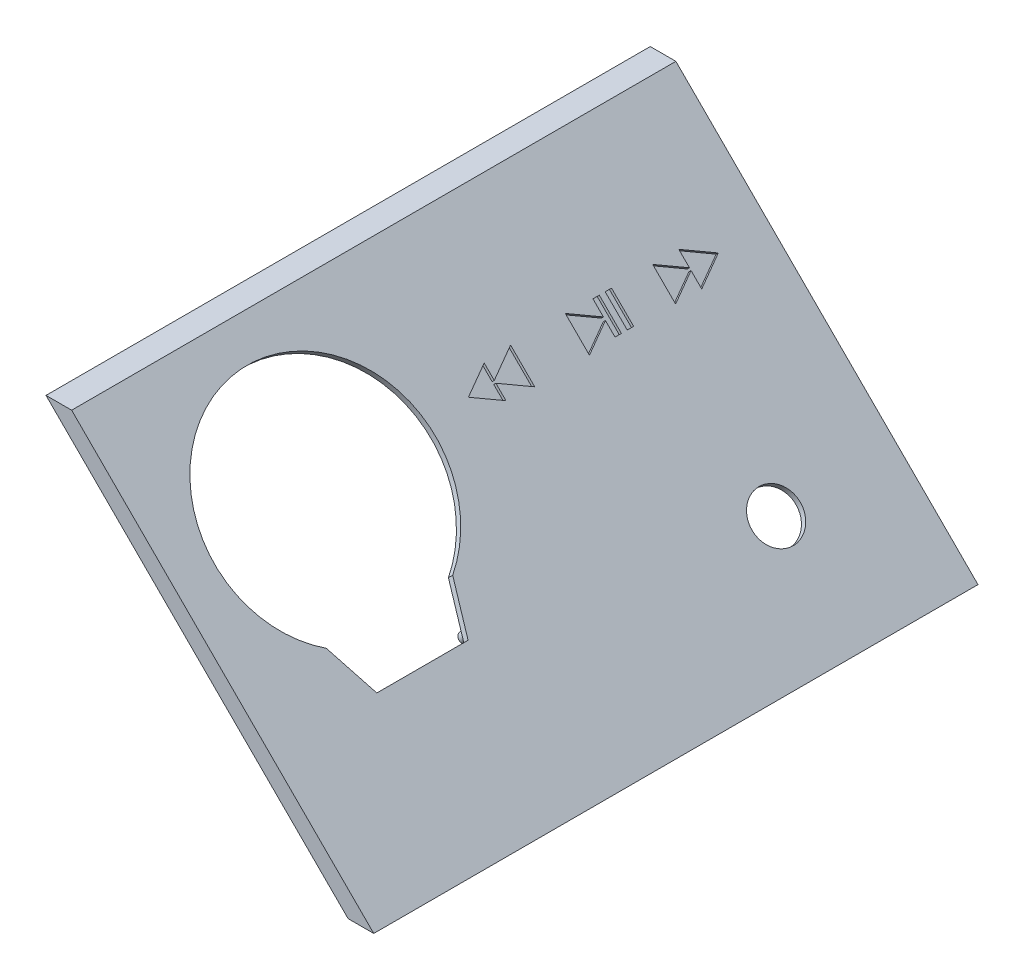
SolidWorks part; units mm, degrees
ref_plane "Front Plane" through (0, 0, 0) normal (0, 0, 1) x (1, 0, 0)
ref_plane "Top Plane" through (0, 0, 0) normal (0, 1, 0) x (1, 0, 0)
ref_plane "Right Plane" through (0, 0, 0) normal (1, 0, 0) x (0, 0, -1)
sketch "Sketch1" plane through (0, 0, 0) normal (0, 0, 1) x (1, 0, 0)
  line L0 (0, 0) -> (4.2426, 0)
  line L1 (4.2426, 0) -> (-45.7574, 50)
  line L2 (-45.7574, 50) -> (-50, 50)
  line L3 (-50, 50) -> (0, 0)
  dimension "D1" = 45
  dimension "D2" = 3
  dimension "D3" = 50
extrude "Boss-Extrude1" add sketch "Sketch1" along normal mid plane 100
sketch "Sketch2" plane through (2.1213, 2.1213, 0) normal (0.7071, 0.7071, 0) x (0, 0, -1)
  line L2 (-50, -3) -> (-50, 67.7107) construction
  line L3 (-32.3831, 21.1966) -> (-17.279, 21.1966)
  line L4 (-17.279, 21.1966) -> (-14.5304, 28.6874)
  line L5 (-32.3831, 21.1966) -> (-35.4536, 28.6762)
  arc A1 (-35.4536, 28.6762) -> (-14.5304, 28.6874) centre (-25, 43.6966) cw
  point P4 (-20.4757, 31.7857)
  point P5 (-38.5206, 31.7857)
  point P13 (-19.0167, 32.7051)
  point P14 (-39.9397, 32.7051)
  dimension "D1" = 18.3
  dimension "D2" = 22.5
  dimension "D3" = 25
extrude "Cut-Extrude1" cut sketch "Sketch2" against normal blind 10
sketch "Sketch3" plane through (2.1213, 2.1213, 0) normal (0.7071, 0.7071, 0) x (0, 0, -1)
  circle A0 centre (29.8486, 15.7517) radius 4
  point P2 (29.4201, 11.6101)
  point P3 (29.8486, 15.7517)
  dimension "D1" = 8
extrude "Cut-Extrude2" cut sketch "Sketch3" against normal blind 10
sketch "Sketch4" plane through (2.1213, 2.1213, 0) normal (0.7071, 0.7071, 0) x (0, 0, -1)
  line L0 (18.2097, 48.6327) -> (18.2097, 42.9848)
  line L1 (18.2097, 42.9848) -> (23.101, 45.8087)
  line L2 (23.101, 45.8087) -> (18.2097, 48.6327)
  line L3 (22.6854, 48.4898) -> (22.6854, 43.324)
  line L4 (22.6854, 43.324) -> (23.7377, 43.324)
  line L5 (23.7377, 43.324) -> (23.7377, 48.4898)
  line L6 (23.7377, 48.4898) -> (22.6854, 48.4898)
  line L7 (24.7108, 48.4898) -> (24.7108, 43.324)
  line L8 (24.7108, 43.324) -> (25.7631, 43.324)
  line L9 (25.7631, 43.324) -> (25.7631, 48.4898)
  line L10 (25.7631, 48.4898) -> (24.7108, 48.4898)
  line L11 (32.5688, 48.4898) -> (32.5688, 43.1276)
  line L12 (32.5688, 43.1276) -> (37.2126, 45.8087)
  line L13 (37.2126, 45.8087) -> (32.5688, 48.4898)
  line L14 (36.891, 48.4898) -> (36.891, 43.1276)
  line L15 (36.891, 43.1276) -> (41.5348, 45.8087)
  line L16 (41.5348, 45.8087) -> (36.891, 48.4898)
  line L17 (9.1516, 48.6327) -> (9.1516, 42.9848)
  line L18 (9.1516, 42.9848) -> (4.2604, 45.8087)
  line L19 (4.2604, 45.8087) -> (9.1516, 48.6327)
  line L20 (4.5903, 48.3554) -> (4.5903, 43.2621)
  line L21 (4.5903, 43.2621) -> (0.1794, 45.8087)
  line L22 (0.1794, 45.8087) -> (4.5903, 48.3554)
  line L23 (-5.6397, 45.8087) -> (45.7193, 45.8087) construction
  point P25 (0, 0)
  point P26 (0, 0)
  point P27 (0, 0)
  point P28 (0, 0)
  point P29 (0, 0)
  point P30 (0, 0)
  point P31 (0, 0)
  point P32 (0, 0)
  dimension "D1" = 60
  dimension "D2" = 60
  dimension "D3" = 60
  dimension "D4" = 60
  dimension "D5" = 60
extrude "Cut-Extrude6" cut sketch "Sketch4" against normal blind 0.5 contours L22 L20 L21 | L19 L17 L18 | L2 L0 L1 | L5 L6 L3 L4 | L9 L10 L7 L8 | L13 L11 L12 | L16 L14 L15
sketch "Sketch5" plane through (0, 0, 0) normal (-0.7071, -0.7071, 0) x (0, 0, 1)
  line L0 (46.201, 64.5251) -> (46.201, 13.4153)
  line L1 (46.201, 13.4153) -> (3.9989, 13.4153)
  line L3 (3.9989, 64.5251) -> (46.201, 64.5251)
  line L4 (3.9989, 54.0276) -> (-43.8621, 54.0276)
  line L5 (-43.8621, 54.0276) -> (-43.8621, 38.2812)
  line L7 (3.9989, 54.0276) -> (3.9989, 64.5251)
  line L9 (3.9989, 13.4153) -> (3.9989, 2.8999)
  line L10 (3.9989, 2.8999) -> (-43.8621, 2.8999)
  line L11 (-43.8621, 2.8999) -> (-43.8621, 38.2812)
extrude "Cut-Extrude7" cut sketch "Sketch5" against normal blind 2
sketch "Sketch6" plane through (2.1213, 2.1213, 0) normal (0.7071, 0.7071, 0) x (0, 0, -1)
  line L0 (-50, -3) -> (-50, 67.7107) construction
  line L1 (-50, -3) -> (50, -3) construction
  circle A0 centre (-34.35, 21.73) radius 0.805
  circle A1 centre (-15.49, 21.73) radius 0.8037
  dimension "D1" = 15.65
  dimension "D2" = 34.51
  dimension "D3" = 24.73
  dimension "D4" = 24.73
extrude "Boss-Extrude2" add sketch "Sketch6" against normal blind 3
